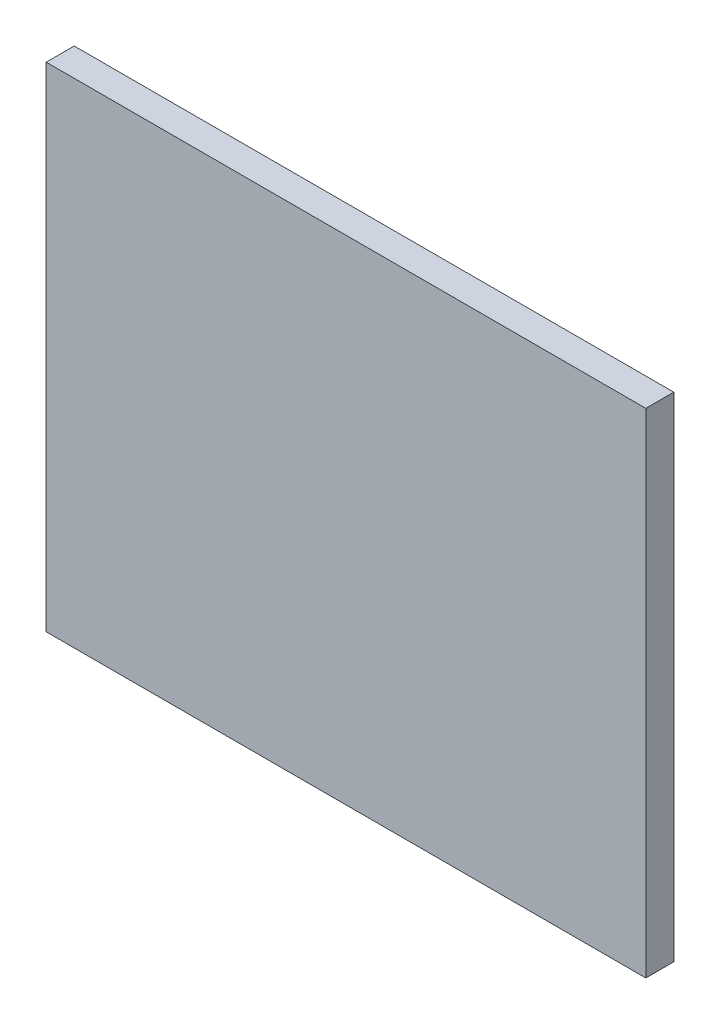
SolidWorks part; units mm, degrees
material "Glass"
ref_plane "Front Plane" through (0, 0, 0) normal (0, 0, 1) x (1, 0, 0)
ref_plane "Top Plane" through (0, 0, 0) normal (0, 1, 0) x (1, 0, 0)
ref_plane "Right Plane" through (0, 0, 0) normal (1, 0, 0) x (0, 0, -1)
sketch "Sketch1" plane through (0, 0, 0) normal (0, 0, 1) x (1, 0, 0)
  line L1 (749.86, -617.01) -> (-749.86, -617.01)
  line L2 (749.86, -617.01) -> (749.86, 617.01)
  line L3 (749.86, 617.01) -> (-749.86, 617.01)
  line L4 (-749.86, -617.01) -> (-749.86, 617.01)
  line L5 (749.86, -617.01) -> (-749.86, 617.01) construction
  line L6 (749.86, 617.01) -> (-749.86, -617.01) construction
  point P0 (0, 0)
  dimension "D1" = 1499.72
  dimension "D2" = 1234.02
extrude "Boss-Extrude1" add sketch "Sketch1" along normal blind 70
